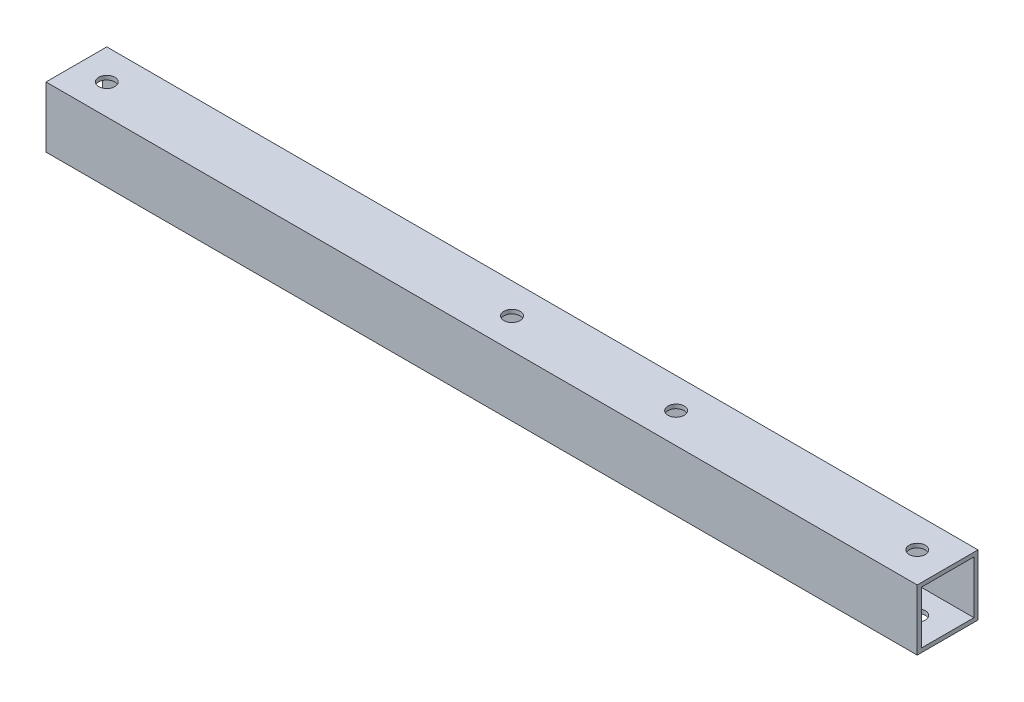
SolidWorks part; units mm, degrees
material "5052-H34"
ref_plane "正面" through (0, 0, 0) normal (0, 0, 1) x (1, 0, 0)
ref_plane "平面" through (0, 0, 0) normal (0, 1, 0) x (1, 0, 0)
ref_plane "右側面" through (0, 0, 0) normal (1, 0, 0) x (0, 0, -1)
sketch "ｽｹｯﾁ1" plane through (0, 0, 0) normal (1, 0, 0) x (0, 0, -1)
  line L1 (0, 0) -> (15, 0)
  line L2 (0, 0) -> (0, 15)
  line L3 (0, 15) -> (15, 15)
  line L4 (15, 0) -> (15, 15)
  dimension "D1" = 15
  dimension "D2" = 15
extrude "押し出し-薄板1" add sketch "ｽｹｯﾁ1" along normal blind 215 thin thin type one direction reverse wall 1
sketch "ｽｹｯﾁ2" plane through (0, 15, 0) normal (0, 1, 0) x (1, 0, 0)
  line L0 (0, 7.5) -> (215, 7.5) construction
  line L1 (0, 15) -> (0, 0) construction
  line L2 (215, 15) -> (215, 0) construction
  line L3 (107.5, 15) -> (107.5, 0) construction
  line L4 (215, 15) -> (0, 15) construction
  line L5 (215, 0) -> (0, 0) construction
  circle A0 centre (107.5, 7.5) radius 2
  circle A1 centre (7.5, 7.5) radius 2
  circle A2 centre (207.5, 7.5) radius 2
  circle A3 centre (148, 7.5) radius 2
  dimension "D1" = 4
  dimension "D2" = 7.5
  dimension "D3" = 67
extrude "ｶｯﾄ - 押し出し1" cut sketch "ｽｹｯﾁ2" against normal up to surface (15 mm away) up to face at (107.5, 0, -7.5)
